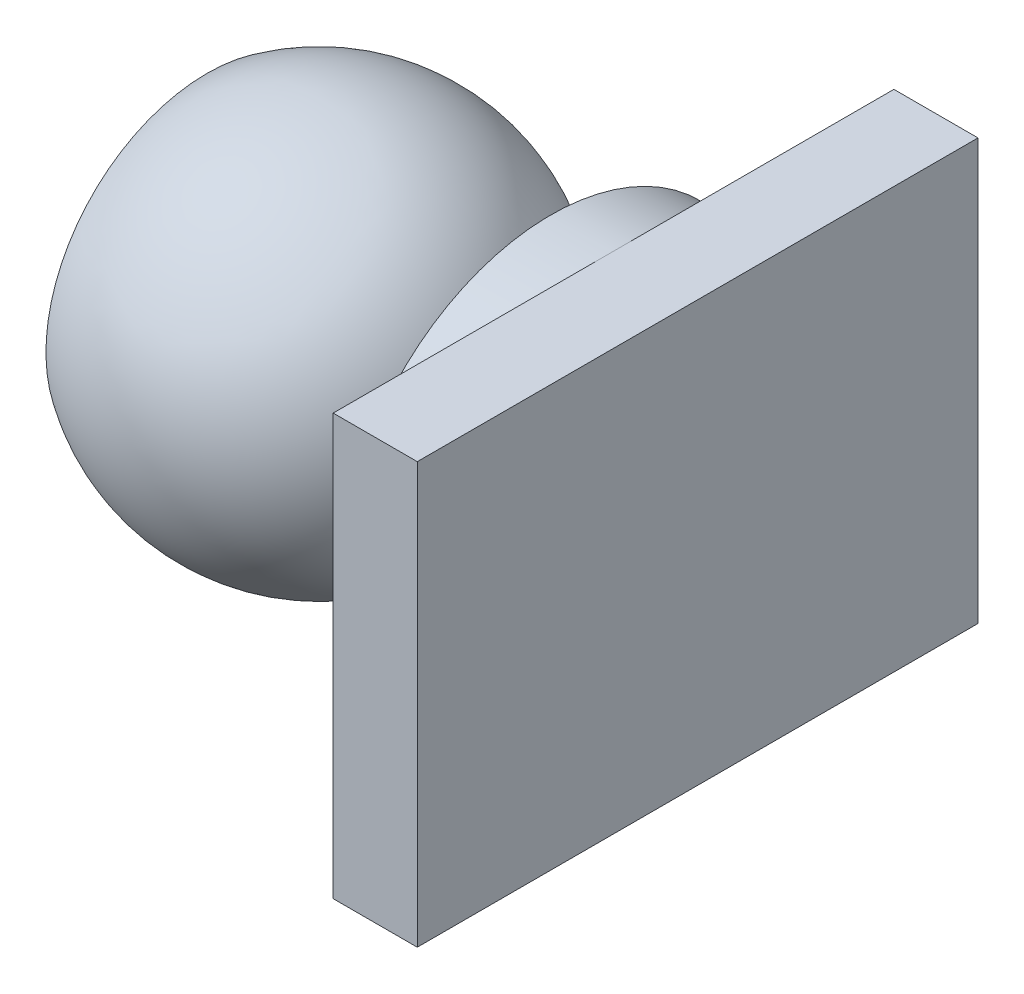
SolidWorks part; units mm, degrees
ref_plane "Alzado" through (0, 0, 0) normal (0, 0, 1) x (1, 0, 0)
ref_plane "Planta" through (0, 0, 0) normal (0, 1, 0) x (1, 0, 0)
ref_plane "Vista lateral" through (0, 0, 0) normal (1, 0, 0) x (0, 0, -1)
sketch "Croquis1" plane through (0, 0, 0) normal (0, 0, 1) x (1, 0, 0)
  line L0 (5.8553, 0) -> (-5.1447, 0)
  line L1 (-5.1447, 5.7446) -> (-5.1447, 0)
  arc A0 (5.8553, 0) -> (-5.1447, 5.7446) centre (-1.1447, 0) ccw
  dimension "D1" = 7
  dimension "D2" = 11
revolve "Revolución1" add sketch "Croquis1" angle 360 about L0
shell "Vaciado1" thickness 0.5
sketch "Croquis2" plane through (0, 0, 0) normal (0, 0, 1) x (1, 0, 0)
  line L0 (5.8553, 0) -> (9.3553, 0)
  line L1 (9.3553, 0) -> (9.3553, -7.5)
  line L2 (9.3553, -7.5) -> (7.1153, -7.5)
  line L3 (0, 0) -> (14.1553, 0) construction
  line L4 (5.8553, 0) -> (5.5326, -2.101)
  arc A0 (-5.1447, -5.7446) -> (-5.1447, 5.7446) centre (-1.1447, 0) ccw construction
  arc A1 (7.1153, -7.5) -> (5.5326, -2.101) centre (-2.8847, -7.5) ccw
  dimension "D4" = 10
  dimension "D1" = 3.5
  dimension "D2" = 2.24
  dimension "D3" = 7.5
revolve "Revolución2" add sketch "Croquis2" angle 360 about L3
sketch "Croquis3" plane through (9.3553, 0, 0) normal (1, 0, 0) x (0, 0, -1)
  line L1 (-10, 7.5) -> (10, 7.5)
  line L2 (-10, 7.5) -> (-10, -7.5)
  line L3 (-10, -7.5) -> (10, -7.5)
  line L4 (10, 7.5) -> (10, -7.5)
  line L5 (-10, 7.5) -> (10, -7.5) construction
  line L6 (-10, -7.5) -> (10, 7.5) construction
  point P0 (0, 0)
  dimension "D1" = 20
  dimension "D2" = 15
extrude "Saliente-Extruir1" add sketch "Croquis3" along normal blind 3
